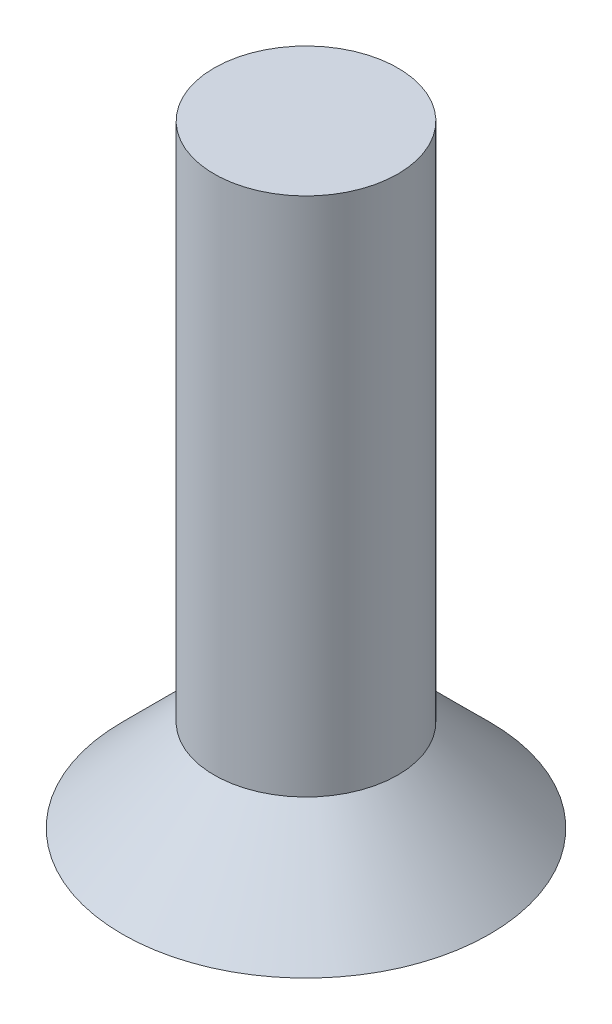
SolidWorks part; units mm, degrees
material "Простая углеродистая сталь"
ref_plane "Спереди" through (0, 0, 0) normal (0, 0, 1) x (1, 0, 0)
ref_plane "Сверху" through (0, 0, 0) normal (0, 1, 0) x (1, 0, 0)
ref_plane "Справа" through (0, 0, 0) normal (1, 0, 0) x (0, 0, -1)
sketch "Эскиз1" plane through (0, 0, 0) normal (0, 0, 1) x (1, 0, 0)
  line L0 (0, 0) -> (-3, 0)
  line L1 (-1.5, 1.5) -> (-1.5, 10)
  line L2 (-3, 0) -> (-1.5, 1.5)
  line L3 (-1.5, 10) -> (0, 10)
  line L4 (0, 10) -> (0, 0)
  dimension "D1" = 3
  dimension "D2" = 45
  dimension "D3" = 10
  dimension "D4" = 1.5
revolve "Конус" add sketch "Эскиз1" angle 360 about L4
